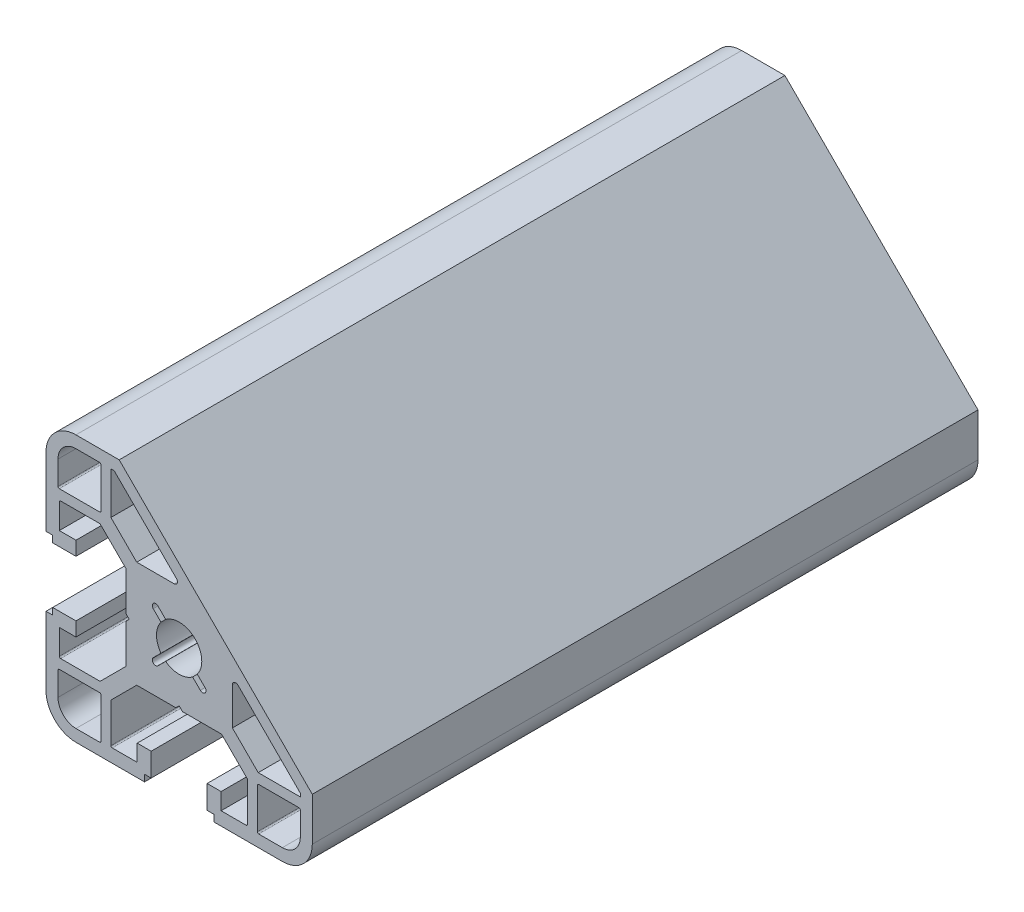
SolidWorks part; units mm, degrees
ref_plane "前视基准面" through (0, 0, 0) normal (0, 0, 1) x (1, 0, 0)
ref_plane "上视基准面" through (0, 0, 0) normal (0, 1, 0) x (1, 0, 0)
ref_plane "右视基准面" through (0, 0, 0) normal (1, 0, 0) x (0, 0, -1)
sketch "草图1" plane through (0, 0, 0) normal (0, 0, 1) x (1, 0, 0)
  line B0 (-20, -15.5) -> (-20, -5.2)
  line B1 (-20, 5.2) -> (-20, 15.5)
  line B2 (-15.5, -20) -> (-5.2, -20)
  line B3 (-15.5, 20) -> (-9.0044, 20)
  line B4 (20, -9.0044) -> (20, -15.5)
  line B5 (-4.2, -19) -> (-4.2, -15.5)
  line B6 (-10.25, -17.8) -> (-10.25, -11.8763)
  line B7 (-10.05, -18) -> (-6.3, -18)
  line B8 (-6.3, -15.5) -> (-4.2, -15.5)
  line B9 (-6.3737, -8) -> (-0.5, -8)
  line B10 (0.5, -8) -> (6.3737, -8)
  line B11 (-6.3, -18) -> (-6.3, -15.5)
  line B12 (-5.2, -19) -> (-5.2, -20)
  line B13 (-5.2, -19) -> (-4.2, -19)
  line B14 (15.5, -20) -> (5.2, -20)
  line B15 (-18.2, -15.5) -> (-18.2, -11.95)
  line B16 (-15.5, -18.2) -> (-11.95, -18.2)
  line B17 (-11.75, -18) -> (-11.75, -11.95)
  line B18 (-18, -11.75) -> (-11.95, -11.75)
  line B19 (-18.2, 15.5) -> (-18.2, 11.95)
  line B20 (-15.5, 18.2) -> (-11.95, 18.2)
  line B21 (-11.75, 18) -> (-11.75, 11.95)
  line B22 (-18, 11.75) -> (-11.95, 11.75)
  line B23 (-6.3737, -8) -> (-10.25, -11.8763)
  line B24 (4.2, -19) -> (4.2, -15.5)
  line B25 (10.25, -17.8) -> (10.25, -11.8763)
  line B26 (10.05, -18) -> (6.3, -18)
  line B27 (6.3, -15.5) -> (4.2, -15.5)
  line B28 (6.3, -18) -> (6.3, -15.5)
  line B29 (5.2, -19) -> (5.2, -20)
  line B30 (5.2, -19) -> (4.2, -19)
  line B31 (6.3737, -8) -> (10.25, -11.8763)
  line B32 (-19, 4.2) -> (-15.5, 4.2)
  line B33 (-17.8, 10.25) -> (-11.8763, 10.25)
  line B34 (-18, 10.05) -> (-18, 6.3)
  line B35 (-15.5, 6.3) -> (-15.5, 4.2)
  line B36 (-8, 6.3737) -> (-8, 0.5)
  line B37 (-8, -0.5) -> (-8, -6.3737)
  line B38 (-18, 6.3) -> (-15.5, 6.3)
  line B39 (-19, 5.2) -> (-20, 5.2)
  line B40 (-19, 5.2) -> (-19, 4.2)
  line B41 (-8, 6.3737) -> (-11.8763, 10.25)
  line B42 (-19, -4.2) -> (-15.5, -4.2)
  line B43 (-17.8, -10.25) -> (-11.8763, -10.25)
  line B44 (-18, -10.05) -> (-18, -6.3)
  line B45 (-15.5, -6.3) -> (-15.5, -4.2)
  line B46 (-18, -6.3) -> (-15.5, -6.3)
  line B47 (-19, -5.2) -> (-20, -5.2)
  line B48 (-19, -5.2) -> (-19, -4.2)
  line B49 (-8, -6.3737) -> (-11.8763, -10.25)
  line B50 (-6.3737, 8) -> (-10.25, 11.8763)
  line B51 (-10.25, 18.2) -> (-10.25, 11.8763)
  line B52 (-10.25, 18.2) -> (-9.75, 18.2)
  line B53 (-0.4036, 8.8536) -> (-9.75, 18.2)
  line B54 (20, -9.0044) -> (-9.0044, 20)
  line B55 (-0.7571, 8) -> (-6.3737, 8)
  line B56 (8, -6.3737) -> (11.8763, -10.25)
  line B57 (18.2, -10.25) -> (11.8763, -10.25)
  line B58 (18.2, -10.25) -> (18.2, -9.75)
  line B59 (8.8536, -0.4036) -> (18.2, -9.75)
  line B60 (8, -0.7571) -> (8, -6.3737)
  line B61 (-0.5, -8) -> (0, -7.5)
  line B62 (0.5, -8) -> (0, -7.5)
  line B63 (-8, 0.5) -> (-7.5, 0)
  line B64 (-8, -0.5) -> (-7.5, 0)
  line B65 (-3.182, -3.8891) -> (-2.0245, -2.7316)
  line B66 (-3.8891, -3.182) -> (-2.7316, -2.0245)
  line B67 (-3.182, 3.8891) -> (-2.0245, 2.7316)
  line B68 (-3.8891, 3.182) -> (-2.7316, 2.0245)
  line B69 (3.182, -3.8891) -> (2.0245, -2.7316)
  line B70 (3.8891, -3.182) -> (2.7316, -2.0245)
  line B71 (15.5, -18.2) -> (11.95, -18.2)
  line B72 (18.2, -15.5) -> (18.2, -11.95)
  line B73 (18, -11.75) -> (11.95, -11.75)
  line B74 (11.75, -18) -> (11.75, -11.95)
  arc B75 (-20, -15.5) -> (-15.5, -20) centre (-15.5, -15.5) ccw
  arc B76 (-18.2, -15.5) -> (-15.5, -18.2) centre (-15.5, -15.5) ccw
  arc B77 (-15.5, 20) -> (-20, 15.5) centre (-15.5, 15.5) ccw
  arc B78 (15.5, -20) -> (20, -15.5) centre (15.5, -15.5) ccw
  arc B79 (-2.0245, -2.7316) -> (2.0245, -2.7316) centre (0, 0) ccw
  arc B80 (2.7316, -2.0245) -> (-2.0245, 2.7316) centre (0, 0) ccw
  arc B81 (-2.7316, 2.0245) -> (-2.7316, -2.0245) centre (0, 0) ccw
  arc B82 (-10.25, -17.8) -> (-10.05, -18) centre (-10.05, -17.8) ccw
  arc B83 (-18, -11.75) -> (-18.2, -11.95) centre (-18, -11.95) ccw
  arc B84 (-11.95, -18.2) -> (-11.75, -18) centre (-11.95, -18) ccw
  arc B85 (-11.75, -11.95) -> (-11.95, -11.75) centre (-11.95, -11.95) ccw
  arc B86 (-15.5, 18.2) -> (-18.2, 15.5) centre (-15.5, 15.5) ccw
  arc B87 (-18.2, 11.95) -> (-18, 11.75) centre (-18, 11.95) ccw
  arc B88 (-11.75, 18) -> (-11.95, 18.2) centre (-11.95, 18) ccw
  arc B89 (-11.95, 11.75) -> (-11.75, 11.95) centre (-11.95, 11.95) ccw
  arc B90 (10.05, -18) -> (10.25, -17.8) centre (10.05, -17.8) ccw
  arc B91 (-17.8, 10.25) -> (-18, 10.05) centre (-17.8, 10.05) ccw
  arc B92 (-18, -10.05) -> (-17.8, -10.25) centre (-17.8, -10.05) ccw
  arc B93 (-0.7571, 8) -> (-0.4036, 8.8536) centre (-0.7571, 8.5) ccw
  arc B94 (8.8536, -0.4036) -> (8, -0.7571) centre (8.5, -0.7571) ccw
  arc B95 (-3.8891, -3.182) -> (-3.182, -3.8891) centre (-3.5355, -3.5355) ccw
  arc B96 (-3.182, 3.8891) -> (-3.8891, 3.182) centre (-3.5355, 3.5355) ccw
  arc B97 (3.182, -3.8891) -> (3.8891, -3.182) centre (3.5355, -3.5355) ccw
  arc B98 (15.5, -18.2) -> (18.2, -15.5) centre (15.5, -15.5) ccw
  arc B99 (11.75, -18) -> (11.95, -18.2) centre (11.95, -18) ccw
  arc B100 (18.2, -11.95) -> (18, -11.75) centre (18, -11.95) ccw
  arc B101 (11.95, -11.75) -> (11.75, -11.95) centre (11.95, -11.95) ccw
sketch_block_instance "A$C132A7E5B-1"
sketch_block "A$C132A7E5B"
extrude "凸台-拉伸1" add sketch "草图1" along normal blind 100
